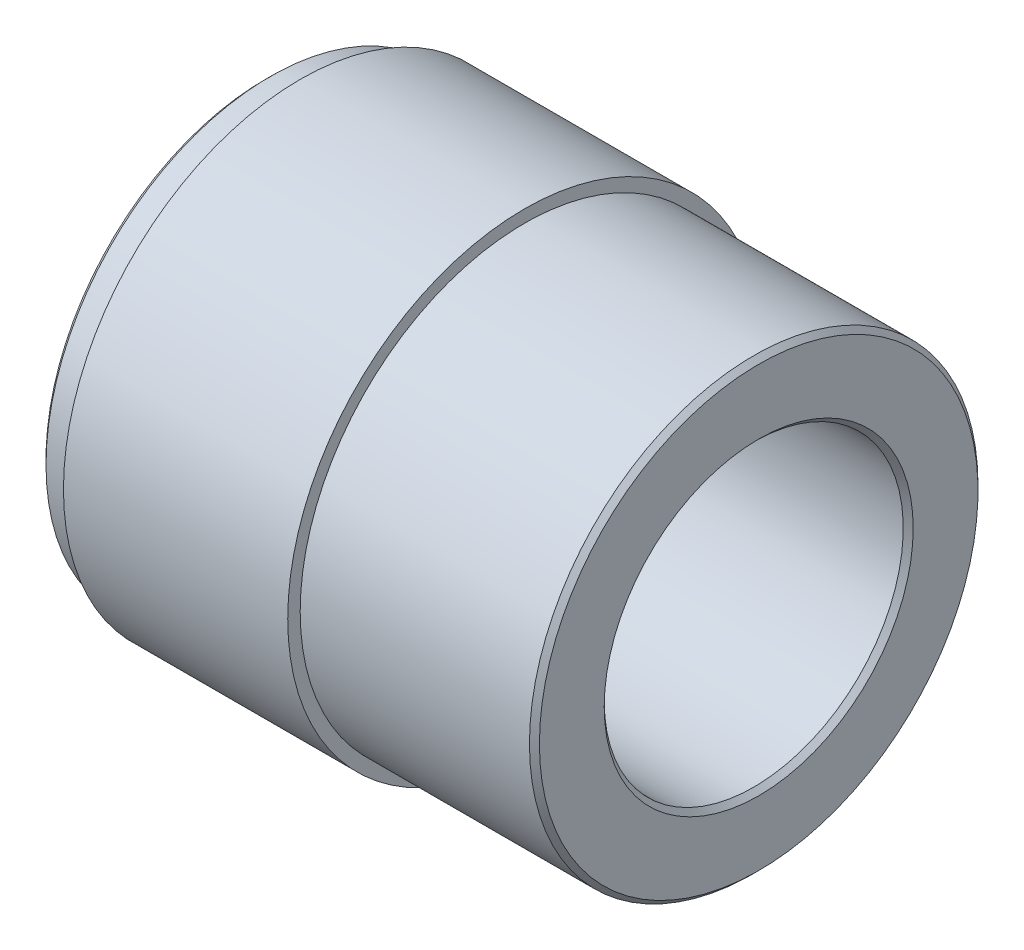
SolidWorks part; units mm, degrees
material "20"
ref_plane "前视基准面" through (0, 0, 0) normal (0, 0, 1) x (1, 0, 0)
ref_plane "上视基准面" through (0, 0, 0) normal (0, 1, 0) x (1, 0, 0)
ref_plane "右视基准面" through (0, 0, 0) normal (1, 0, 0) x (0, 0, -1)
sketch "草图1" plane through (0, 0, 0) normal (0, 0, 1) x (1, 0, 0)
  line L0 (0, 0) -> (99, 0) construction
  line L1 (0, 45) -> (7, 45)
  line L2 (7, 45) -> (7, 47.5)
  line L3 (7, 47.5) -> (52, 47.5)
  line L4 (52, 47.5) -> (52, 45)
  line L5 (52, 45) -> (99, 45)
  line L6 (0, 45) -> (0, 30)
  line L8 (99, 30) -> (99, 45)
  line L9 (0, 30) -> (4.5, 30)
  line L10 (4.5, 30) -> (4.5, 31.5)
  line L11 (4.5, 31.5) -> (6.7, 31.5)
  line L12 (6.7, 31.5) -> (6.7, 30)
  line L13 (6.7, 30) -> (99, 30)
  dimension "D1" = 99
  dimension "D2" = 45
  dimension "D3" = 47
  dimension "D4" = 30
  dimension "D5" = 45
  dimension "D6" = 47.5
  dimension "D7" = 4.5
  dimension "D8" = 2.2
  dimension "D9" = 1.5
revolve "旋转1" add sketch "草图1" angle 360 about L0
chamfer "倒角1" distance 1 angle 45 4 edges at (99, 0, 30) (99, 0, 45) (0, 0, 45) (0, 0, 30)
